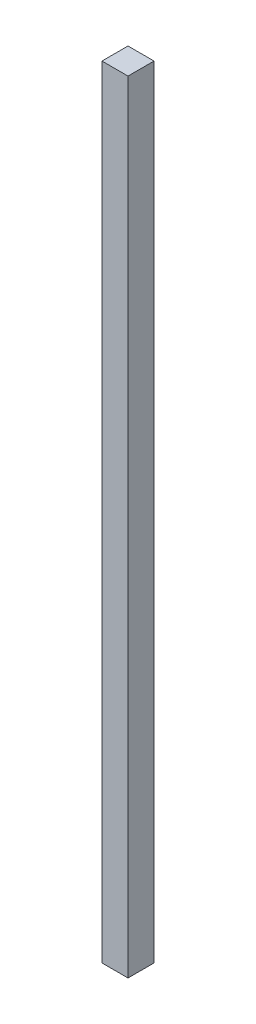
SolidWorks part; units mm, degrees
ref_plane "前视基准面" through (0, 0, 0) normal (0, 0, 1) x (1, 0, 0)
ref_plane "上视基准面" through (0, 0, 0) normal (0, 1, 0) x (1, 0, 0)
ref_plane "右视基准面" through (0, 0, 0) normal (1, 0, 0) x (0, 0, -1)
other "Configuration Table"
sketch "草图1" plane through (0, 0, 0) normal (0, 1, 0) x (1, 0, 0)
  line L1 (0, 0) -> (5, 0)
  line L2 (0, 0) -> (0, 5)
  line L3 (0, 5) -> (5, 5)
  line L4 (5, 0) -> (5, 5)
  dimension "D1" = 5
  dimension "D2" = 5
extrude "凸台-拉伸1" add sketch "草图1" along normal blind 150
